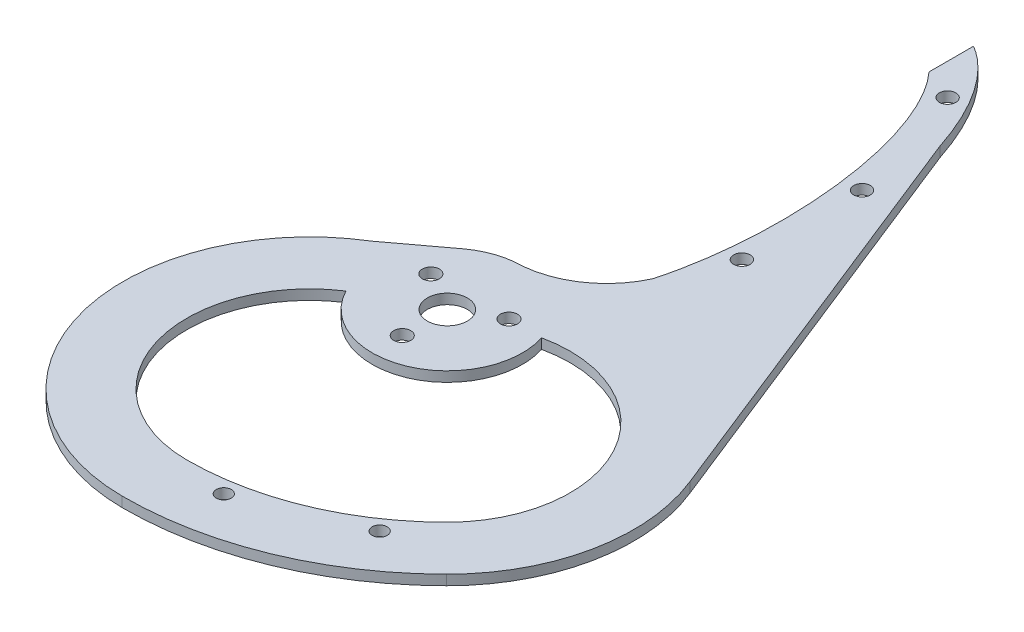
SolidWorks part; units mm, degrees
ref_plane "Спереди" through (0, 0, 0) normal (0, 0, 1) x (1, 0, 0)
ref_plane "Сверху" through (0, 0, 0) normal (0, 1, 0) x (1, 0, 0)
ref_plane "Справа" through (0, 0, 0) normal (1, 0, 0) x (0, 0, -1)
sketch "Эскиз1" plane through (0, 0, 0) normal (0, 1, 0) x (1, 0, 0)
  line L0 (0, 0) -> (0, -55) construction
  line L1 (9.5506, -54.1644) -> (0, 0) construction
  line L2 (0, 0) -> (35.7004, -86.1885) construction
  line L3 (53.9586, -5.5613) -> (20.9296, 77.346)
  line L4 (0, 0) -> (0, 100) construction
  line L5 (0, 93) -> (0, 100) construction
  line L6 (-19.3568, 4.2687) -> (-8.973, 12.0202)
  line L7 (0, 0) -> (38.8909, -38.8909) construction
  line L8 (0, 0) -> (-20.1763, 11.6488) construction
  line L9 (0, 0) -> (0, -14.3061) construction
  line L10 (0, 0) -> (20.2825, 11.7101) construction
  line L11 (7, 98) -> (7, 89.1252)
  arc A0 (45.6624, -45.8385) -> (-0.2166, -64.7007) centre (0, 0) cw
  arc A1 (0, -52) -> (36.7696, -36.7696) centre (0, 0) ccw
  arc A2 (0, -55) -> (55, 0) centre (0, 0) ccw construction
  circle A3 centre (9.5506, -54.1644) radius 1.5
  circle A4 centre (31.5467, -45.0534) radius 1.5
  circle A5 centre (19.4454, -19.4454) radius 24.5 construction
  circle A6 centre (0, 0) radius 4
  arc A7 (0, 15) -> (15.1926, 25.8295) centre (-1.7823, 33.5719) ccw
  arc A8 (0, 15) -> (-8.973, 12.0202) centre (0, 0) ccw
  arc A9 (-4.5095, -14.3061) -> (14.3061, 4.5095) centre (0, 0) ccw
  arc A10 (36.7696, -36.7696) -> (14.3061, 4.5095) centre (19.4454, -19.4454) ccw
  arc A11 (-19.3568, 4.2687) -> (-0.2166, -64.7007) centre (0, -27.5) ccw
  arc A12 (45.6624, -45.8385) -> (53.9586, -5.5613) centre (19.4454, -19.4454) ccw
  circle A13 centre (0, 0) radius 9 construction
  circle A14 centre (0, -9) radius 1.7
  circle A15 centre (-7.7942, 4.5) radius 1.7
  circle A16 centre (0, -27.5) radius 24.5 construction
  circle A17 centre (0, 0) radius 10.7 construction
  arc A18 (0, -52) -> (-13.3046, -6.9273) centre (0, -27.5) cw
  circle A19 centre (7.7942, 4.5) radius 1.7
  arc A20 (-13.3046, -6.9273) -> (-4.5095, -14.3061) centre (0, 0) ccw
  ellipse E0 centre (0, 50) end of major axis (0.6459, 6.982) minor radius 18.002 (15.1926, 25.8295) -> (0, 93) ccw construction
  ellipse E1 centre (0, 50) end of major axis (-0.6459, 93.018) minor radius 18.002 (15.1926, 25.8295) -> (7, 89.1252) ccw
  ellipse E2 centre (0, 50) end of major axis (0, 100) minor radius 25 (20.9296, 77.346) -> (7, 98) ccw
  ellipse E3 centre (0, 50) end of major axis (0.004, 0) minor radius 25 (20.9205, 77.3689) -> (0, 100) ccw construction
  point P25 (-0.6653, 12.4183)
  point P54 (0, 0)
  dimension "D2" = 55
  dimension "D3" = 52
  dimension "D4" = 3
  dimension "D7" = 50
  dimension "D8" = 15
  dimension "D9" = 8
  dimension "D10" = 7
  dimension "D11" = 18
  dimension "D12" = 25
  dimension "D13" = 21.4
  dimension "D14" = 120
  dimension "D5" = 10
  dimension "D6" = 22.5
  dimension "D15" = 120
  dimension "D16" = 7
extrude "Бобышка-Вытянуть1" add sketch "Эскиз1" along normal blind 2
sketch "Эскиз2" plane through (0, 0, 0) normal (0, -1, 0) x (1, 0, 0)
  line L0 (0, 0) -> (0, -100) construction
  line L1 (0, -50) -> (47.6456, -22.4918) construction
  line L2 (0, -50) -> (19.0233, -102.2662) construction
  line L3 (0, -50) -> (48.7895, -78.1686) construction
  circle A0 centre (20.7726, -38.0069) radius 1.65
  circle A1 centre (13.2986, -86.5376) radius 1.65
  circle A2 centre (20.7726, -61.9931) radius 1.65
  ellipse E1 centre (0, -50) end of major axis (0, -3.5) minor radius 21.5 construction
  dimension "D3" = 3.3
  dimension "D4" = 3.3
  dimension "D5" = 3.3
  dimension "D1" = 120
  dimension "D2" = 20
  dimension "D6" = 60
extrude "Вырез-Вытянуть1" cut sketch "Эскиз2" against normal through all
